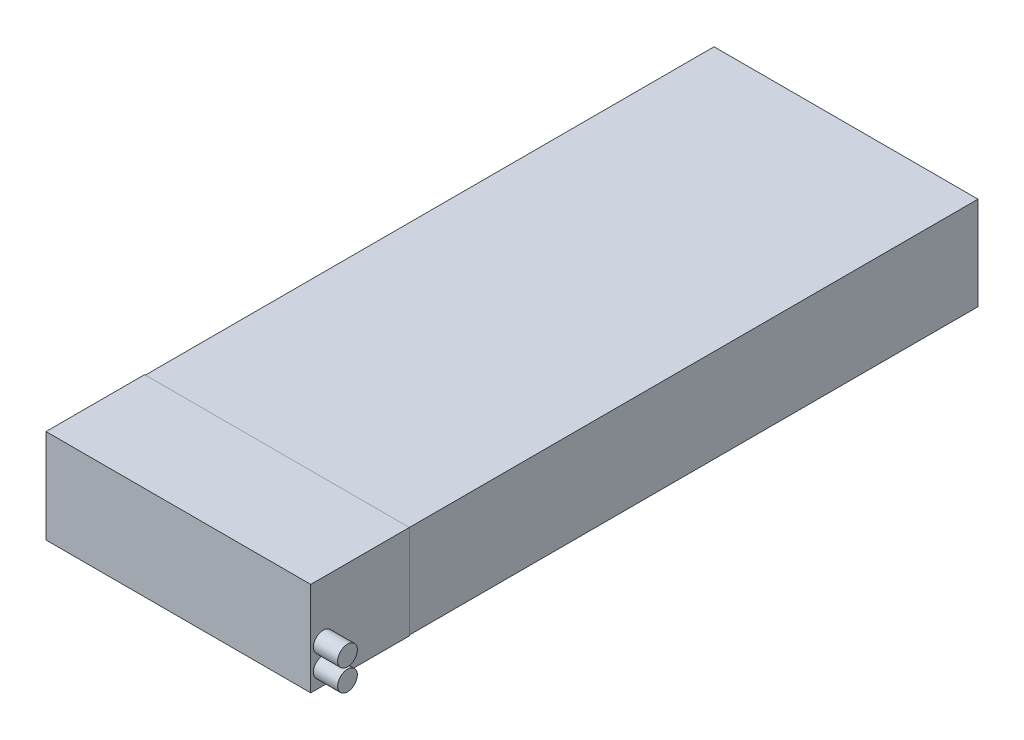
SolidWorks part; units mm, degrees
ref_plane "Front Plane" through (0, 0, 0) normal (0, 0, 1) x (1, 0, 0)
ref_plane "Top Plane" through (0, 0, 0) normal (0, 1, 0) x (1, 0, 0)
ref_plane "Right Plane" through (0, 0, 0) normal (1, 0, 0) x (0, 0, -1)
sketch "Sketch1" plane through (0, 0, 0) normal (0, 0, 1) x (1, 0, 0)
  line L1 (0, 0) -> (17, 0)
  line L2 (0, 0) -> (0, 6)
  line L3 (0, 6) -> (17, 6)
  line L4 (17, 0) -> (17, 6)
  dimension "D1" = 6
  dimension "D2" = 17
extrude "Boss-Extrude1" add sketch "Sketch1" along normal blind 43
sketch "Sketch3" plane through (0, 0, 43) normal (0, 0, 1) x (1, 0, 0)
  line L0 (0, 6) -> (0, 0) construction
  line L1 (-0.0254, 6.0254) -> (17.0254, 6.0254)
  line L2 (-0.0254, 6.0254) -> (-0.0254, -0.0254)
  line L3 (-0.0254, -0.0254) -> (17.0254, -0.0254)
  line L4 (17.0254, 6.0254) -> (17.0254, -0.0254)
  line L5 (17, 0) -> (17, 6) construction
  line L6 (17, 6) -> (0, 6) construction
  line L7 (0, 0) -> (17, 0) construction
  dimension "D1" = 0.0254
  dimension "D2" = 0.0254
  dimension "D3" = 0.0254
  dimension "D4" = 0.0254
extrude "Boss-Extrude2" add sketch "Sketch3" against normal blind 6.35
sketch "Sketch4" plane through (17, 0, 0) normal (1, 0, 0) x (0, 0, -1)
  circle A0 centre (-42.1938, 1.0412) radius 0.635
  circle A1 centre (-42.1938, 2.4382) radius 0.635
  dimension "D1" = 1.27
  dimension "D2" = 1.397
extrude "Boss-Extrude4" add sketch "Sketch4" along normal blind 1.5875 contours A0 A1 | A1 A0 | A0 A1
